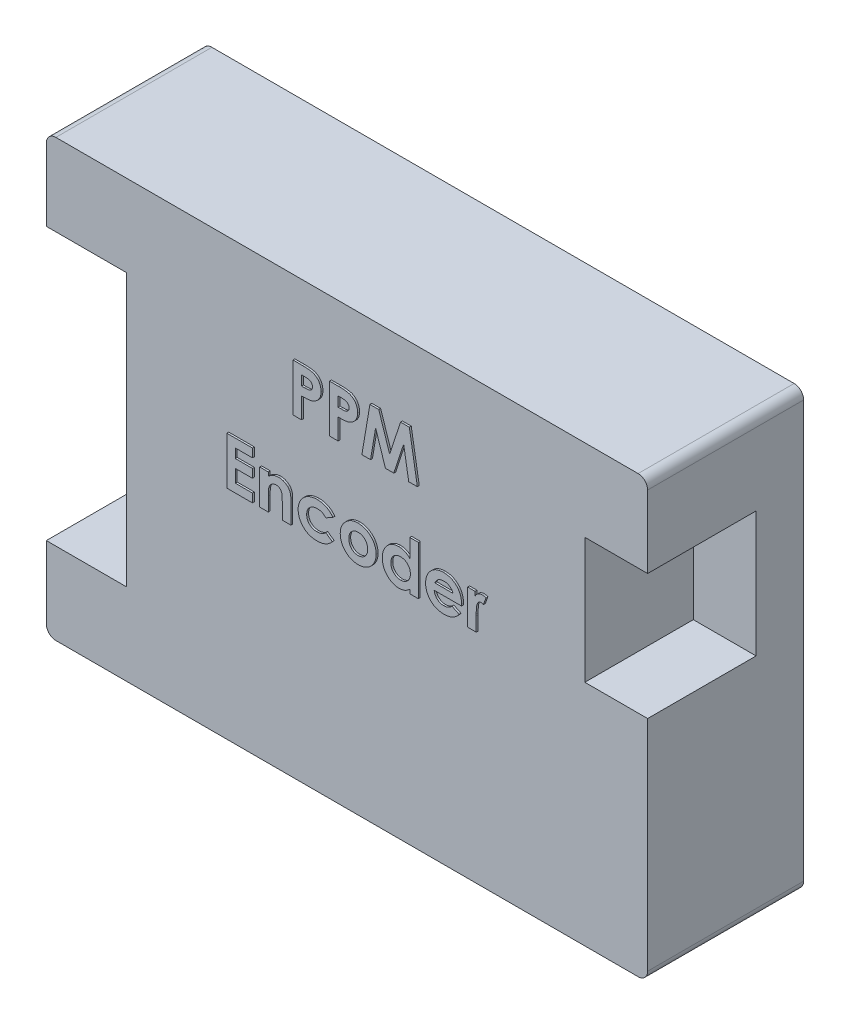
SolidWorks part; units mm, degrees
material "Polyester Resin"
ref_plane "Front Plane" through (0, 0, 0) normal (0, 0, 1) x (1, 0, 0)
ref_plane "Top Plane" through (0, 0, 0) normal (0, 1, 0) x (1, 0, 0)
ref_plane "Right Plane" through (0, 0, 0) normal (1, 0, 0) x (0, 0, -1)
sketch "Sketch1" plane through (0, 0, 0) normal (0, 0, 1) x (1, 0, 0)
  line L1 (-15.8, -11.45) -> (15.8, -11.45)
  line L2 (-15.8, -11.45) -> (-15.8, 11.45)
  line L3 (-15.8, 11.45) -> (15.8, 11.45)
  line L4 (15.8, -11.45) -> (15.8, 11.45)
  point P4 (0, 0)
  point P5 (0, 11.45)
  point P8 (15.8, 0)
  dimension "D1" = 22.9
  dimension "D2" = 31.6
extrude "Boss-Extrude1" add sketch "Sketch1" along normal mid plane 8.2 contours L2 L1 L4 L3
sketch "Sketch2" plane through (0, 0, 4.1) normal (0, 0, 1) x (1, 0, 0)
  line L0 (-15.8, 7.15) -> (-11.6, 7.15)
  line L1 (-15.8, -11.45) -> (-15.8, 11.45) construction
  line L2 (-11.6, 7.15) -> (-11.6, -7.15)
  line L3 (-11.6, -7.15) -> (-15.8, -7.15)
  line L4 (15.8, 7.15) -> (12.5, 7.15)
  line L5 (15.8, -11.45) -> (15.8, 11.45) construction
  line L6 (12.5, 7.15) -> (12.5, 0.55)
  line L7 (12.5, 0.55) -> (15.8, 0.55)
  line L8 (15.8, 0.55) -> (15.8, 7.15)
  line L9 (-15.8, 7.15) -> (-15.8, -7.15)
  line L10 (-15.8, 11.45) -> (15.8, 11.45) construction
  dimension "D1" = 4.3
  dimension "D2" = 6.6
  dimension "D3" = 3.3
  dimension "D4" = 4.2
  dimension "D5" = 14.3
  dimension "D6" = 4.3
extrude "Cut-Extrude1" cut sketch "Sketch2" against normal offset from surface (5.7 mm away) 2.5 contours L9 L3 L2 L0 | L8 L4 L6 L7 up to face at (0, 0, -4.1)
fillet "Fillet1" radius 0.5 4 edges at (-15.8, 11.45, 0) (15.8, 11.45, 0) (-15.8, -11.45, 0) (15.8, -11.45, 0)
sketch "Sketch3" plane through (0, 0, 4.1) normal (0, 0, 1) x (1, 0, 0)
  line L0 (-11.6, 5.1491) -> (12.5, 5.1491) construction
  line L1 (-11.6, 7.15) -> (-11.6, -7.15) construction
  line L2 (12.5, 7.15) -> (12.5, 0.55) construction
  line L3 (-9.5112, 11.45) -> (-9.5112, -11.45) construction
  line L4 (-15.3, 11.45) -> (15.3, 11.45) construction
  line L5 (-15.3, -11.45) -> (15.3, -11.45) construction
  line L6 (8.9021, 11.45) -> (8.9021, 0.55) construction
  text T0 "PPM\r\nEncoder" font "Century Gothic" height 2.5
extrude "Boss-Extrude2" add sketch "Sketch3" along normal blind 0.1
